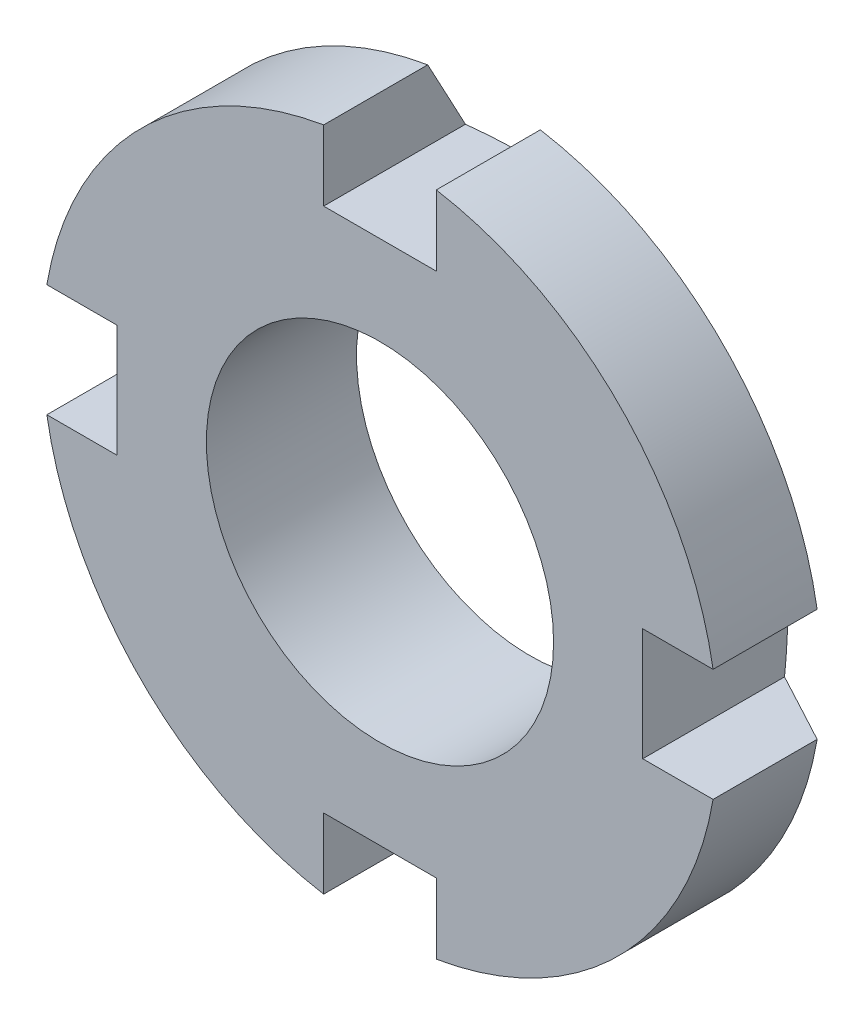
SolidWorks part; units mm, degrees
ref_plane "Front Plane" through (0, 0, 0) normal (0, 0, 1) x (1, 0, 0)
ref_plane "Top Plane" through (0, 0, 0) normal (0, 1, 0) x (1, 0, 0)
ref_plane "Right Plane" through (0, 0, 0) normal (1, 0, 0) x (0, 0, -1)
ref_axis "Axis1" through (0, 0, 4.2) along (0, 0, -1)
sketch "Sketch1" plane through (0, 0, 0) normal (0, 0, 1) x (1, 0, 0)
  circle A0 centre (0, 0) radius 9
extrude "Boss-Extrude1" add sketch "Sketch1" along normal blind 4 contours A0
sketch "Sketch2" plane through (0, 0, 0) normal (1, 0, 0) x (0, 0, -1)
  line L0 (-1.2277, 9) -> (0, 6.75)
  line L1 (0, 9) -> (-1.2277, 9)
  line L2 (0, 9) -> (0, 6.75)
sketch "Sketch3" plane through (0, 0, 4) normal (0, 0, 1) x (1, 0, 0)
  line L1 (-1.5, 9) -> (1.5, 9)
  line L2 (-1.5, 9) -> (-1.5, 7)
  line L3 (-1.5, 7) -> (1.5, 7)
  line L4 (1.5, 9) -> (1.5, 7)
  line L5 (-1.5, 9) -> (1.5, 7) construction
  line L6 (-1.5, 7) -> (1.5, 9) construction
  point P4 (0, 8)
extrude "Cut-Extrude1" cut sketch "Sketch3" against normal through all
pattern_circular "CirPattern1" count 4 over 360 about axis through (0, 0, 0) along (0, 0, 1) of "Cut-Extrude1"
revolve "Cut-Revolve1" cut sketch "Sketch2" angle 360 about axis through (0, 0, 4.2) along (0, 0, -1)
sketch "Sketch11" plane through (0, 0, 4) normal (0, 0, 1) x (1, 0, 0)
  point P0 (0, 0)
hole_wizard "M10x1.0 Tapped Hole1" positions "Sketch11" profile "Sketch12" tap size "M10x1.0" standard "JIS" end condition up to next
cosmetic thread "Hole Thread1" parameters "D2"=10
sketch "Sketch12" plane through (0, 0, 4) normal (1, 0, 0) x (0, -1, 0)
  line L0 (0, 0) -> (0, 4)
  line L1 (0, 4) -> (4.5, 4)
  line L2 (4.5, 4) -> (4.5, 0)
  line L5 (4.5, 0) -> (0, 0)
  line L11 (0, -6.35) -> (0, 107.95) construction
  dimension "Thru Tap Drill Dia." = 9
  dimension "Thru Tap Drill Depth" = 4
sketch "Sketch4" plane through (0, 0, 4) normal (0, 0, 1) x (1, 0, 0)
  circle A0 centre (0, 0) radius 4.625
extrude "Cut-Extrude2" cut sketch "Sketch4" against normal through all
